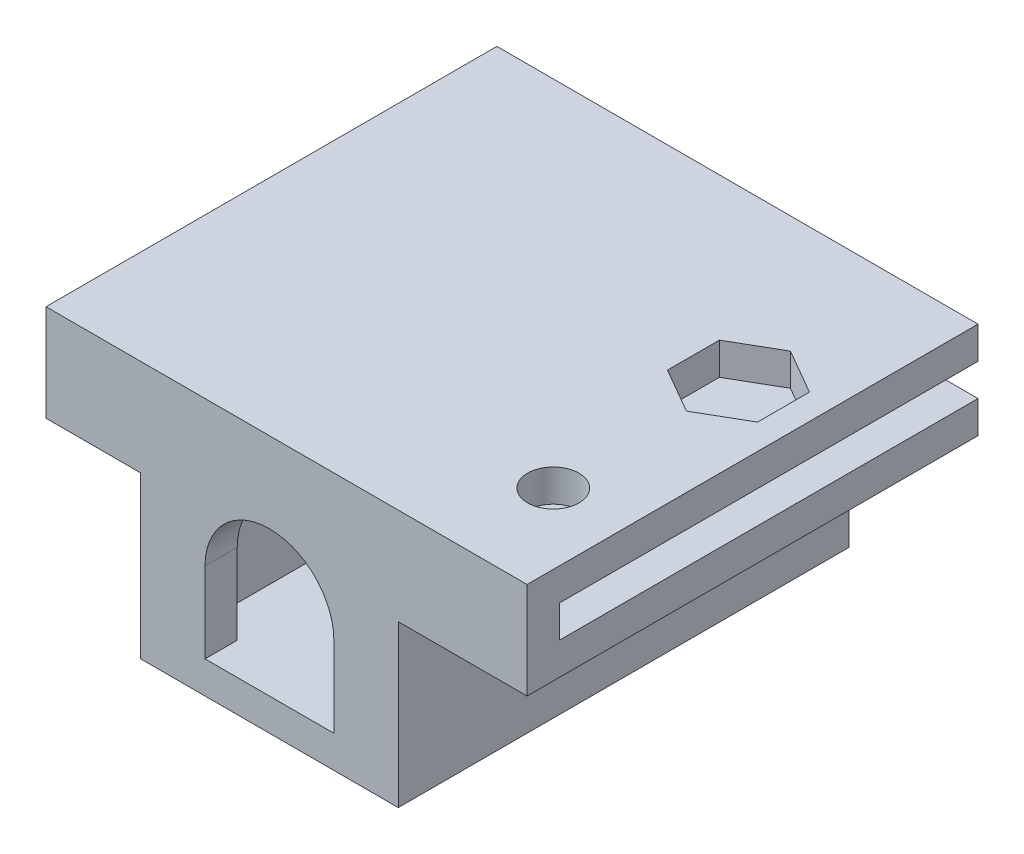
SolidWorks part; units mm, degrees
ref_plane "前视基准面" through (0, 0, 0) normal (0, 0, 1) x (1, 0, 0)
ref_plane "上视基准面" through (0, 0, 0) normal (0, 1, 0) x (1, 0, 0)
ref_plane "右视基准面" through (0, 0, 0) normal (1, 0, 0) x (0, 0, -1)
sketch "草图1" plane through (0, 0, 0) normal (0, 0, 1) x (1, 0, 0)
  line L0 (8, 3) -> (16, 3)
  line L1 (8, -7) -> (-8, -7)
  line L2 (8, -7) -> (8, 3)
  line L3 (8, 5) -> (-8, 5)
  line L4 (6, -4) -> (6, 4)
  line L5 (5, 5) -> (-5, 5)
  line L6 (-6, 4) -> (-6, -4)
  line L7 (-5, -5) -> (5, -5)
  line L8 (6, -4) -> (6, 4)
  line L9 (5, 5) -> (-5, 5)
  line L10 (-6, 4) -> (-6, -4)
  line L11 (-5, -5) -> (5, -5)
  line L12 (88.125, 7) -> (-11.875, 7)
  line L13 (-11.875, 7) -> (-11.875, 5)
  line L14 (-11.875, 5) -> (88.125, 5)
  line L15 (88.125, 5) -> (88.125, 7)
  line L16 (88.125, 7) -> (-11.875, 7)
  line L17 (-11.875, 7) -> (-11.875, 5)
  line L18 (-11.875, 5) -> (88.125, 5)
  line L19 (88.125, 5) -> (88.125, 7)
  line L20 (-8, -7) -> (-8, 3)
  line L21 (-13.875, 3) -> (-8, 3)
  line L22 (-13.875, 3) -> (-13.875, 9)
  line L23 (-13.875, 9) -> (16, 9)
  line L24 (16, 3) -> (16, 9)
  line L26 (4, 0) -> (4, -5)
  line L27 (4, -5) -> (-4, -5)
  line L28 (-4, 0) -> (-4, -5)
  arc A0 (4, 0) -> (-4, 0) centre (0, 0) ccw
  arc A4 (6, 4) -> (5, 5) centre (5, 4) ccw
  arc A5 (-5, 5) -> (-6, 4) centre (-5, 4) ccw
  arc A6 (-6, -4) -> (-5, -5) centre (-5, -4) ccw
  arc A7 (5, -5) -> (6, -4) centre (5, -4) ccw
  arc A8 (6, 4) -> (5, 5) centre (5, 4) ccw
  arc A9 (-5, 5) -> (-6, 4) centre (-5, 4) ccw
  arc A10 (-6, -4) -> (-5, -5) centre (-5, -4) ccw
  arc A11 (5, -5) -> (6, -4) centre (5, -4) ccw
  dimension "D5" = 2
  dimension "D6" = 2
  dimension "D1" = 0
  dimension "D2" = 0
extrude "凸台-拉伸1" add sketch "草图1" along normal blind 2 contours A11 L11 A10 L10 A9 L3 L18 L17 L16 L24 L23 L22 L21 L20 L1 L2 L0 A8 L8 | L18 L24 L16 L17 L3 | L11 A11 L8 A8 L3 A9 L10 A10 L28 A0 L26
sketch "草图2" plane through (0, 0, 0) normal (0, 0, -1) x (-1, 0, 0)
  line L1 (6, -5) -> (-6, -5)
  line L2 (6, -5) -> (6, 5)
  line L3 (6, 5) -> (-6, 5)
  line L4 (-6, 4) -> (-6, -4)
  line L5 (5, 5) -> (-5, 5)
  line L6 (6, -4) -> (6, 4)
  line L7 (-5, -5) -> (5, -5)
  line L8 (-6, 4) -> (-6, -4)
  line L9 (5, 5) -> (-5, 5)
  line L10 (6, -4) -> (6, 4)
  line L11 (-5, -5) -> (5, -5)
  line L12 (-16, 9) -> (-16, 3)
  line L13 (-16, 3) -> (-8, 3)
  line L14 (-8, 3) -> (-8, -7)
  line L15 (-8, -7) -> (8, -7)
  line L16 (8, -7) -> (8, 3)
  line L17 (8, 3) -> (13.875, 3)
  line L18 (13.875, 3) -> (13.875, 9)
  line L19 (13.875, 9) -> (-16, 9)
  line L23 (11.875, 7) -> (-88.125, 7)
  line L24 (-16, 9) -> (-16, 3)
  line L25 (-16, 3) -> (-8, 3)
  line L26 (-8, 3) -> (-8, -7)
  line L27 (-8, -7) -> (8, -7)
  line L28 (8, -7) -> (8, 3)
  line L29 (8, 3) -> (13.875, 3)
  line L30 (13.875, 3) -> (13.875, 9)
  line L31 (13.875, 9) -> (-16, 9)
  line L36 (-6, -5) -> (-6, 5)
  line L37 (11.875, 5) -> (11.875, 7)
  line L38 (-88.125, 5) -> (11.875, 5)
  line L39 (-88.125, 7) -> (-88.125, 5)
  line L40 (11.875, 7) -> (-88.125, 7)
  line L41 (11.875, 5) -> (11.875, 7)
  line L42 (-88.125, 5) -> (11.875, 5)
  line L43 (-88.125, 7) -> (-88.125, 5)
  arc A4 (-5, 5) -> (-6, 4) centre (-5, 4) ccw
  arc A5 (6, 4) -> (5, 5) centre (5, 4) ccw
  arc A6 (5, -5) -> (6, -4) centre (5, -4) ccw
  arc A7 (-6, -4) -> (-5, -5) centre (-5, -4) ccw
  arc A8 (-5, 5) -> (-6, 4) centre (-5, 4) ccw
  arc A9 (6, 4) -> (5, 5) centre (5, 4) ccw
  arc A10 (5, -5) -> (6, -4) centre (5, -4) ccw
  arc A11 (-6, -4) -> (-5, -5) centre (-5, -4) ccw
  dimension "D1" = 0
  dimension "D2" = 0
  dimension "D3" = 0
extrude "凸台-拉伸2" add sketch "草图2" along normal offset from surface (26 mm away) 2
sketch "草图3" plane through (0, 0, -26) normal (0, 0, -1) x (-1, 0, 0)
  line L1 (6, -5) -> (-6, -5)
  line L2 (6, -5) -> (6, -4)
  line L3 (6, -4) -> (-6, -4)
  line L4 (-6, -5) -> (-6, -4)
  line L20 (-16, 5) -> (-16, 3)
  line L21 (-16, 3) -> (-8, 3)
  line L22 (-8, 3) -> (-8, -7)
  line L23 (-8, -7) -> (8, -7)
  line L24 (8, -7) -> (8, 3)
  line L25 (8, 3) -> (13.875, 3)
  line L26 (13.875, 3) -> (13.875, 9)
  line L27 (13.875, 9) -> (-16, 9)
  line L28 (6, 5) -> (6, -5)
  line L29 (6, 5) -> (6, -5)
  line L30 (6, -5) -> (-6, -5)
  line L31 (6, -5) -> (-6, -5)
  line L36 (-16, 5) -> (-16, 3)
  line L37 (-16, 3) -> (-8, 3)
  line L38 (-8, 3) -> (-8, -7)
  line L39 (-8, -7) -> (8, -7)
  line L40 (8, -7) -> (8, 3)
  line L41 (8, 3) -> (13.875, 3)
  line L42 (13.875, 3) -> (13.875, 9)
  line L43 (13.875, 9) -> (-16, 9)
  line L48 (-6, -5) -> (-6, 5)
  line L49 (-6, -5) -> (-6, 5)
  line L50 (-6, 5) -> (-16, 5)
  line L51 (-6, 5) -> (-16, 5)
  line L52 (-16, 9) -> (-16, 7)
  line L53 (-16, 9) -> (-16, 7)
  line L54 (-16, 7) -> (11.875, 7)
  line L55 (-16, 7) -> (11.875, 7)
  line L56 (11.875, 7) -> (11.875, 5)
  line L57 (11.875, 7) -> (11.875, 5)
  line L58 (11.875, 5) -> (6, 5)
  line L59 (11.875, 5) -> (6, 5)
  line M19 (6, 5) -> (6, -5)
  line M20 (6, -5) -> (-6, -5)
  line M21 (-6, -5) -> (-6, 5)
  dimension "D2" = 1
  dimension "D1" = 0
extrude "凸台-拉伸3" add sketch "草图3" against normal blind 1.6 contours L3 M19 M21 M20
sketch "草图4" plane through (0, 9, 0) normal (0, 1, 0) x (1, 0, 0)
  line L0 (13.92, 16.825) -> (9.33, 14.175) construction
  line L2 (11.625, 12.2726) -> (14.42, 13.8863)
  line L3 (14.42, 13.8863) -> (14.42, 17.1137)
  line L4 (16, -2) -> (16, 26)
  line L5 (16, 26) -> (-13.875, 26)
  line L6 (-13.875, 26) -> (-13.875, -2)
  line L7 (-13.875, -2) -> (16, -2)
  line L8 (16, -2) -> (16, 26)
  line L9 (16, 26) -> (-13.875, 26)
  line L10 (-13.875, 26) -> (-13.875, -2)
  line L11 (-13.875, -2) -> (16, -2)
  line L12 (14.42, 17.1137) -> (11.625, 18.7274)
  line L13 (11.625, 18.7274) -> (8.83, 17.1137)
  line L14 (11.625, 18.15) -> (9.33, 16.825)
  line L15 (9.33, 16.825) -> (9.33, 14.175)
  line L16 (9.33, 14.175) -> (11.625, 12.85)
  line L17 (11.625, 12.85) -> (13.92, 14.175)
  line L18 (13.92, 14.175) -> (13.92, 16.825)
  line L19 (13.92, 16.825) -> (11.625, 18.15)
  line L20 (11.625, 18.15) -> (9.33, 16.825)
  line L21 (9.33, 16.825) -> (9.33, 14.175)
  line L22 (9.33, 14.175) -> (11.625, 12.85)
  line L23 (11.625, 12.85) -> (13.92, 14.175)
  line L24 (13.92, 14.175) -> (13.92, 16.825)
  line L25 (13.92, 16.825) -> (11.625, 18.15)
  line L26 (8.83, 17.1137) -> (8.83, 13.8863)
  line L27 (8.83, 13.8863) -> (11.625, 12.2726)
  circle A0 centre (11.625, 15.5) radius 2.795 construction
  dimension "D3" = 0.5
  dimension "D1" = 0
  dimension "D2" = 0
extrude "切除-拉伸1" cut sketch "草图4" against normal blind 2 contours L2 L3 L12 L13 L26 L27
sketch "草图5" plane through (0, 3, 0) normal (0, -1, 0) x (1, 0, 0)
  line L0 (11.625, -18.6754) -> (11.625, 2) construction
  line L1 (11.625, -18.6754) -> (14.375, -17.0877)
  line L2 (14.375, -17.0877) -> (14.375, -13.9123)
  line L3 (14.375, -13.9123) -> (11.625, -12.3246)
  line L4 (8, 2) -> (8, -26)
  line L5 (8, -26) -> (16, -26)
  line L6 (16, -26) -> (16, 2)
  line L7 (16, 2) -> (8, 2)
  line L8 (8, 2) -> (8, -26)
  line L9 (8, -26) -> (16, -26)
  line L10 (16, -26) -> (16, 2)
  line L11 (16, 2) -> (8, 2)
  line L12 (11.625, -12.3246) -> (8.875, -13.9123)
  line L13 (8.875, -13.9123) -> (8.875, -17.0877)
  line L14 (8.875, -17.0877) -> (11.625, -18.6754)
  circle A0 centre (11.625, -15.5) radius 1.25 construction
  circle A1 centre (11.625, -15.5) radius 1.25
  circle A2 centre (11.625, -15.5) radius 2.75 construction
  dimension "D2" = 5.5
  dimension "D1" = 0
extrude "切除-拉伸2" cut sketch "草图5" against normal blind 0.5 contours L12 L13 L14 L1 L2 L3
sketch "草图6" plane through (0, 3, 0) normal (0, -1, 0) x (1, 0, 0)
  line L0 (11.625, -18.6754) -> (11.625, 2) construction
  line L1 (14.375, -17.0877) -> (8.875, -13.9123) construction
  line L2 (8.625, -5.7321) -> (11.625, -7.4641)
  line L3 (11.625, -7.4641) -> (14.625, -5.7321)
  line L4 (8, 2) -> (8, -26)
  line L5 (8, -26) -> (16, -26)
  line L6 (16, -26) -> (16, 2)
  line L7 (16, 2) -> (8, 2)
  line L8 (8, 2) -> (8, -26)
  line L9 (8, -26) -> (16, -26)
  line L10 (16, -26) -> (16, 2)
  line L11 (16, 2) -> (8, 2)
  line L12 (14.625, -5.7321) -> (14.625, -2.2679)
  line L13 (14.625, -2.2679) -> (11.625, -0.5359)
  line L14 (14.375, -13.9123) -> (11.625, -12.3246)
  line L15 (11.625, -12.3246) -> (8.875, -13.9123)
  line L16 (8.875, -13.9123) -> (8.875, -17.0877)
  line L17 (8.875, -17.0877) -> (11.625, -18.6754)
  line L18 (11.625, -18.6754) -> (14.375, -17.0877)
  line L19 (14.375, -17.0877) -> (14.375, -13.9123)
  line L20 (14.375, -13.9123) -> (11.625, -12.3246)
  line L21 (11.625, -12.3246) -> (8.875, -13.9123)
  line L22 (8.875, -13.9123) -> (8.875, -17.0877)
  line L23 (8.875, -17.0877) -> (11.625, -18.6754)
  line L24 (11.625, -18.6754) -> (14.375, -17.0877)
  line L25 (14.375, -17.0877) -> (14.375, -13.9123)
  line L26 (11.625, -0.5359) -> (8.625, -2.2679)
  line L27 (8.625, -2.2679) -> (8.625, -5.7321)
  circle A0 centre (11.625, -4) radius 3 construction
  point P6 (11.625, -15.5)
  dimension "D3" = 6
  dimension "D4" = 11.5
  dimension "D1" = 0
  dimension "D2" = 0
extrude "切除-拉伸3" cut sketch "草图6" against normal blind 1 contours L2 L3 L12 L13 L26 L27
sketch "草图7" plane through (0, 4, 0) normal (0, -1, 0) x (1, 0, 0)
  line L0 (8.625, -2.2679) -> (8.625, -5.7321) construction
  line L1 (8.625, -5.7321) -> (11.625, -7.4641) construction
  line L2 (11.625, -7.4641) -> (14.625, -5.7321) construction
  line L3 (14.625, -5.7321) -> (14.625, -2.2679) construction
  line L4 (14.625, -2.2679) -> (11.625, -0.5359) construction
  line L5 (11.625, -0.5359) -> (8.625, -2.2679) construction
  line L6 (14.375, -13.9123) -> (11.625, -12.3246) construction
  line L7 (11.625, -12.3246) -> (8.875, -13.9123) construction
  line L8 (8.875, -13.9123) -> (8.875, -17.0877) construction
  line L9 (8.875, -17.0877) -> (11.625, -18.6754) construction
  line L10 (11.625, -18.6754) -> (14.375, -17.0877) construction
  line L11 (14.375, -17.0877) -> (14.375, -13.9123) construction
  line L12 (8.625, -2.2679) -> (8.625, -5.7321)
  line L13 (8.625, -5.7321) -> (11.625, -7.4641)
  line L14 (11.625, -7.4641) -> (14.625, -5.7321)
  line L15 (14.625, -5.7321) -> (14.625, -2.2679)
  line L16 (14.625, -2.2679) -> (11.625, -0.5359)
  line L17 (11.625, -0.5359) -> (8.625, -2.2679)
  line L18 (14.375, -13.9123) -> (11.625, -12.3246)
  line L19 (11.625, -12.3246) -> (8.875, -13.9123)
  line L20 (8.875, -13.9123) -> (8.875, -17.0877)
  line L21 (8.875, -17.0877) -> (11.625, -18.6754)
  line L22 (11.625, -18.6754) -> (14.375, -17.0877)
  line L23 (14.375, -17.0877) -> (14.375, -13.9123)
  line L24 (11.625, -7.4641) -> (11.625, -0.5359) construction
  circle A0 centre (11.625, -15.5) radius 1.35
  circle A1 centre (11.625, -4) radius 1.6
  dimension "D1" = 3.2
  dimension "D2" = 2.7
extrude "切除-拉伸4" cut sketch "草图7" against normal through all and the other way blind 1 contours A0 | A1
